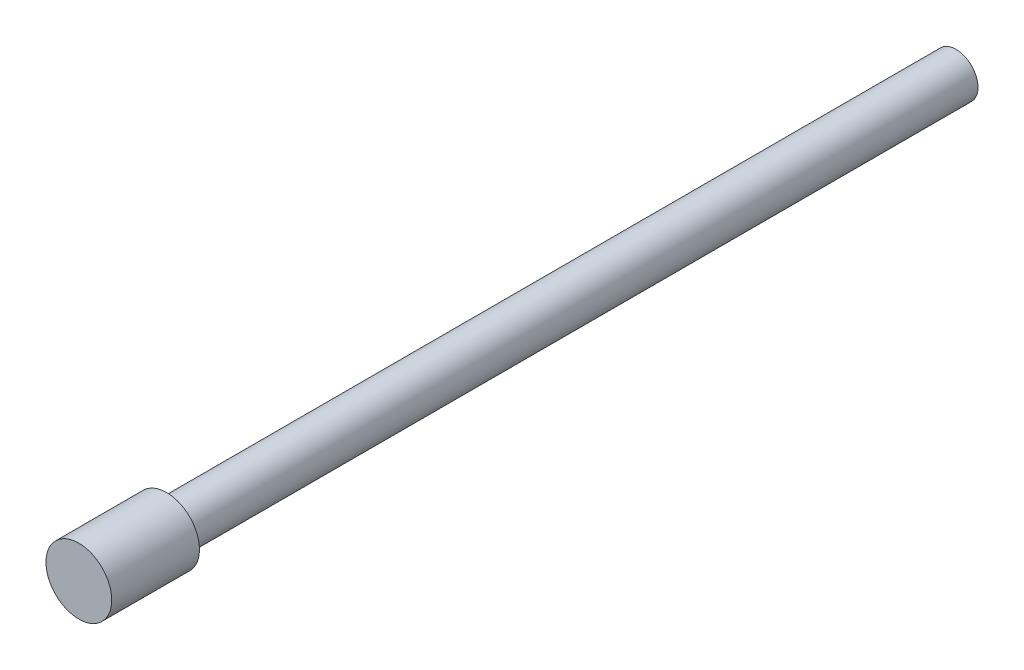
SolidWorks part; units mm, degrees
ref_plane "Plano frontal" through (0, 0, 0) normal (0, 0, 1) x (1, 0, 0)
ref_plane "Plano superior" through (0, 0, 0) normal (0, 1, 0) x (1, 0, 0)
ref_plane "Plano direito" through (0, 0, 0) normal (1, 0, 0) x (0, 0, -1)
sketch "Esboço1" plane through (0, 0, 0) normal (0, 0, 1) x (1, 0, 0)
  circle A0 centre (0, 0) radius 7.5
  dimension "D1" = 15
extrude "Ressalto-extrusão1" add sketch "Esboço1" against normal blind 20
sketch "Esboço9" plane through (0, 0, -20) normal (0, 0, -1) x (-1, 0, 0)
  circle A0 centre (0, 0) radius 5
  dimension "D1" = 10
extrude "Ressalto-extrusão3" add sketch "Esboço9" along normal blind 180
